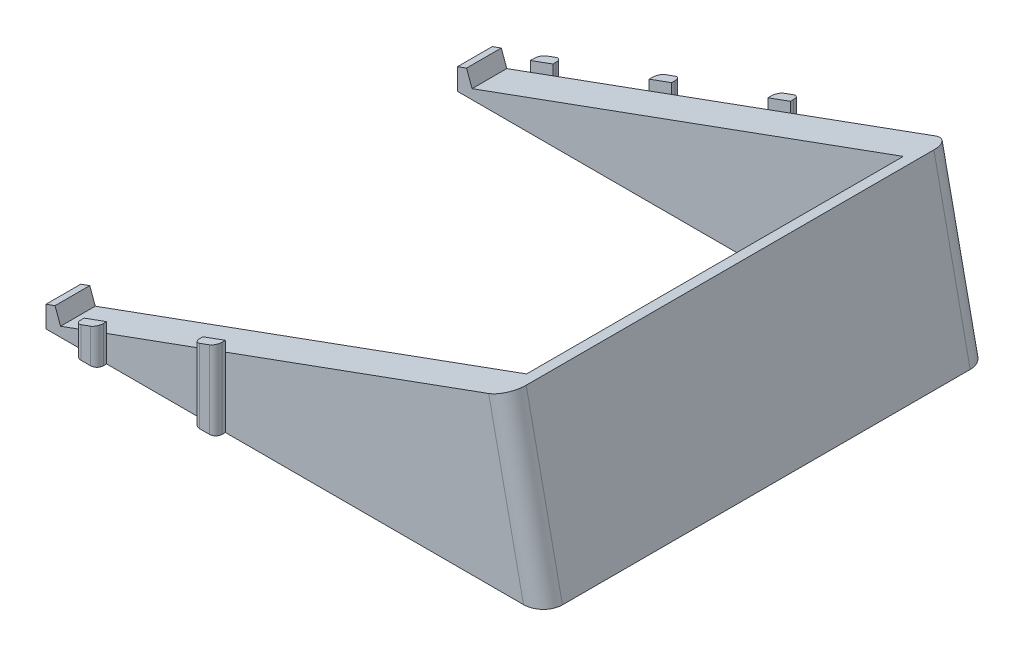
SolidWorks part; units mm, degrees
ref_plane "Front Plane" through (0, 0, 0) normal (0, 0, 1) x (1, 0, 0)
ref_plane "Top Plane" through (0, 0, 0) normal (0, 1, 0) x (1, 0, 0)
ref_plane "Right Plane" through (0, 0, 0) normal (1, 0, 0) x (0, 0, -1)
sketch "base-outline" plane through (0, 0, 0) normal (0, 1, 0) x (1, 0, 0)
  line L0 (0, 0) -> (30, 0)
  line L1 (173, 0) -> (173, 139)
  line L2 (173, 139) -> (111, 139)
  line L3 (0, 139) -> (0, 128.18)
  line L4 (0, 128.18) -> (157, 128.18)
  line L5 (157, 128.18) -> (157, 10.82)
  line L6 (157, 10.82) -> (0, 10.82)
  line L7 (0, 10.82) -> (0, 0)
  line L8 (37, 0) -> (67, 0)
  line L10 (30, 139) -> (30, 142)
  line L11 (30, 142) -> (37, 142)
  line L12 (37, 139) -> (37, 142)
  line L14 (67, 139) -> (67, 142)
  line L15 (67, 142) -> (74, 142)
  line L16 (74, 139) -> (74, 142)
  line L18 (104, 139) -> (104, 142)
  line L19 (104, 142) -> (111, 142)
  line L20 (111, 139) -> (111, 142)
  line L22 (30, 0) -> (30, -3)
  line L23 (30, -3) -> (37, -3)
  line L24 (37, 0) -> (37, -3)
  line L26 (74, 0) -> (74, -3)
  line L27 (74, -3) -> (67, -3)
  line L28 (67, 0) -> (67, -3)
  line L33 (74, 0) -> (111, 0)
  line L34 (111, 0) -> (173, 0)
  line L35 (30, 139) -> (0, 139)
  line L36 (67, 139) -> (37, 139)
  line L37 (104, 139) -> (74, 139)
  point P10 (74, -1.5)
  point P34 (37, 140.5)
  dimension "D1" = 30
  dimension "D2" = 7
  dimension "D13" = 3
  dimension "D14" = 0
  dimension "D16" = 3
  dimension "D3" = 10.82
  dimension "D4" = 10.82
  dimension "D5" = 173
  dimension "D6" = 16
  dimension "D7" = 139
  dimension "D8" = 3
  dimension "D9" = 7
  dimension "D10" = 7
  dimension "D11" = 30
  dimension "D12" = 30
  dimension "D17" = 3
  dimension "D18" = 30
  dimension "D20" = 7
  dimension "D21" = 7
  dimension "D22" = 30
  dimension "D24" = 74
extrude "Boss-Extrude1" add sketch "base-outline" along normal blind 100
sketch "tent-angle" plane through (0, 0, 0) normal (0, 0, 1) x (1, 0, 0)
  line L0 (173, 57.7232) -> (22.6492, 3)
  line L3 (22.6492, 0) -> (173, 0)
  line L4 (173, 0) -> (173, 57.7232)
  line L5 (173, 100) -> (173, 0) construction
  line L6 (0, 0) -> (157, 0) construction
  line L7 (22.6492, 3) -> (20.9391, 7.6985)
  line L8 (20.9391, 7.6985) -> (18.12, 6.6724)
  line L9 (18.12, 6.6724) -> (18.12, 0)
  line L10 (18.12, 0) -> (22.6492, 0)
  dimension "D1" = 160
  dimension "D2" = 3
  dimension "D3" = 20
  dimension "D4" = 90
  dimension "D5" = 5
  dimension "D6" = 3
extrude "Cut-Extrude1" cut sketch "tent-angle" against normal up to vertex (139 mm away) flip side to cut contours L0 L7 L8 L9 L10 L3 L4 up to point (67, 100, -139)
sketch "middle-angle" plane through (0, 0, 0) normal (0, 0, 1) x (1, 0, 0)
  line L1 (30, 5.6755) -> (22.6492, 3) construction
  line L16 (30, 5.6755) -> (22.6492, 3) construction
  line L18 (161.6985, 53.6098) -> (173, 0)
  line L19 (173, 57.7232) -> (173, 0)
  line L20 (161.6985, 53.6098) -> (173, 57.7232)
  line L21 (30, 5.6755) -> (22.6492, 3) construction
  dimension "D1" = 5
extrude "Cut-Extrude3" cut sketch "middle-angle" against normal blind 200
fillet "Fillet1" radius 6 1 edges at (167.3492, 26.8049, 0)
fillet "Fillet2" radius 6 1 edges at (167.3492, 26.8049, -139)
sketch "feet-inset" plane through (0, 0, 0) normal (0, -1, 0) x (1, 0, 0)
  line L0 (157, -10.82) -> (18.12, -10.82) construction
  line L1 (18.12, -128.18) -> (157, -128.18) construction
  line L2 (157, -128.18) -> (157, -10.82) construction
  circle A0 centre (45, -5.32) radius 4.25
  circle A1 centre (165, -5.32) radius 4.25
  circle A2 centre (165, -133.68) radius 4.25
  circle A3 centre (45, -133.68) radius 4.25
  dimension "D4" = 8.5
  dimension "D5" = 8.5
  dimension "D6" = 8.5
  dimension "D7" = 8.5
  dimension "D1" = 120
  dimension "D2" = 5.5
  dimension "D3" = 5.5
  dimension "D8" = 0
  dimension "D9" = 8
  dimension "D10" = 8
  dimension "D11" = 5.5
  dimension "D12" = 120
extrude "Cut-Extrude4" cut sketch "feet-inset" against normal blind 0.6
fillet "Fillet3" radius 2 10 edges at (37, 50, -142) (30, 50, -142) (67, 50, -142) (74, 50, -142) (104, 50, -142) (111, 50, -142) (74, 50, 3) (67, 50, 3) (37, 50, 3) (30, 50, 3)
sketch "keyboard-seat" plane through (0, 0, 0) normal (0, 0, 1) x (1, 0, 0)
  line L0 (22.6492, 3) -> (20.9391, 7.6985) construction
  line L1 (21.6231, 5.8191) -> (160.6724, 56.4289)
  line L2 (160.6724, 56.4289) -> (161.6985, 53.6098)
  line L5 (156.0036, 51.537) -> (74, 21.6902) construction
  line L6 (21.6231, 5.8191) -> (-12.5789, 99.7883)
  line L7 (-12.5789, 99.7883) -> (126.4704, 150.3981)
  line L8 (126.4704, 150.3981) -> (160.6724, 56.4289)
  dimension "D1" = 90
  dimension "D3" = 3
  dimension "D4" = 100
  dimension "D5" = 90
extrude "Cut-Extrude5" cut sketch "keyboard-seat" against normal blind 200 and the other way blind 40 contours L8 L7 L6 L1
